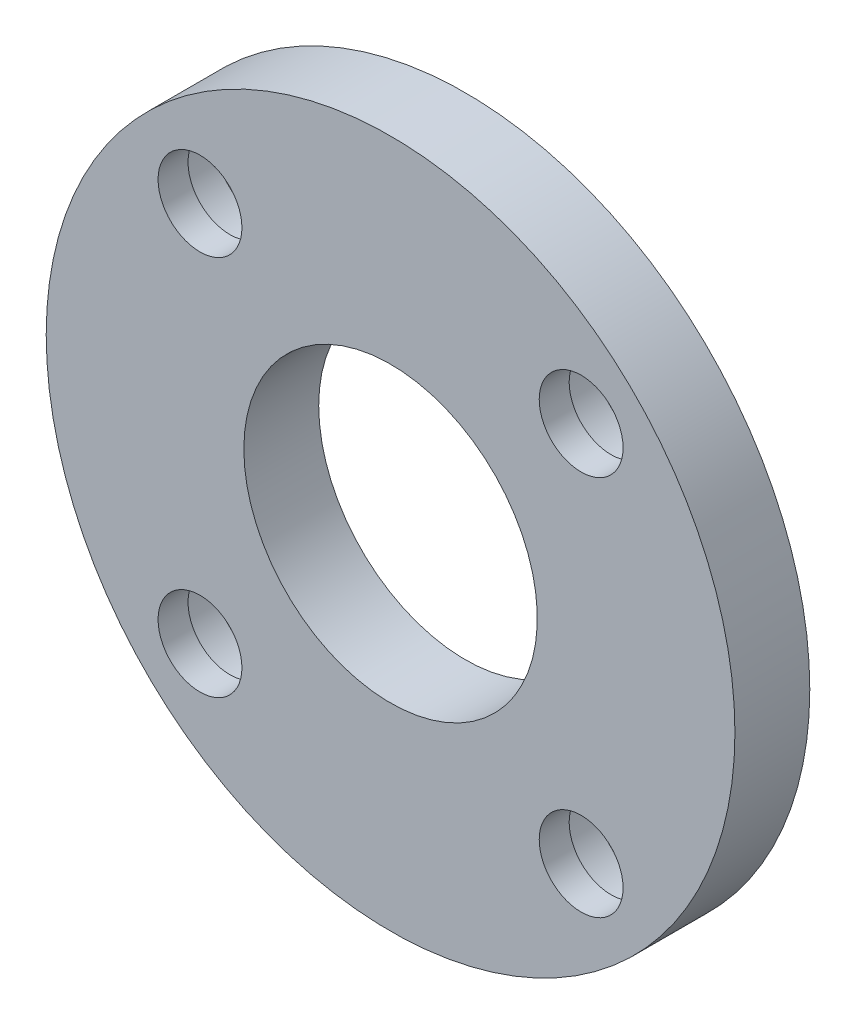
SolidWorks part; units mm, degrees
ref_plane "Piano frontale" through (0, 0, 0) normal (0, 0, 1) x (1, 0, 0)
ref_plane "Piano superiore" through (0, 0, 0) normal (0, 1, 0) x (1, 0, 0)
ref_plane "Piano destro" through (0, 0, 0) normal (1, 0, 0) x (0, 0, -1)
sketch "Schizzo2" plane through (0, 0, 0) normal (0, 0, 1) x (1, 0, 0)
  circle A1 centre (12.7279, 12.7279) radius 2.8
  circle A2 centre (12.7279, -12.7279) radius 2.8
  circle A3 centre (-12.7279, -12.7279) radius 2.8
  circle A4 centre (-12.7279, 12.7279) radius 2.8
  circle A5 centre (0, 0) radius 23
  circle A6 centre (-12.7279, 12.7279) radius 2.8
  circle A7 centre (12.7279, 12.7279) radius 2.8
  circle A8 centre (12.7279, -12.7279) radius 2.8
  circle A9 centre (-12.7279, -12.7279) radius 2.8
extrude "Estrusione-Estrusione3" add sketch "Schizzo2" along normal blind 5 contours A4 | A1 | A2 | A3 | A5
sketch "Schizzo5" plane through (0, 0, 0) normal (0, 0, -1) x (-1, 0, 0)
  circle A0 centre (-12.7279, 12.7279) radius 4.3
  circle A1 centre (12.7588, 12.7279) radius 4.3
  circle A2 centre (12.7279, -12.7279) radius 4.3
  circle A3 centre (-12.7279, -12.7279) radius 4.3
extrude "Taglio-Estrusione1" cut sketch "Schizzo5" against normal blind 3 contours A3 | A2 | A1 | A0
sketch "Schizzo6" plane through (0, 0, 0) normal (0, 0, -1) x (-1, 0, 0)
  circle A0 centre (0, 0) radius 9.8
extrude "Taglio-Estrusione2" cut sketch "Schizzo6" against normal through all contours A0
